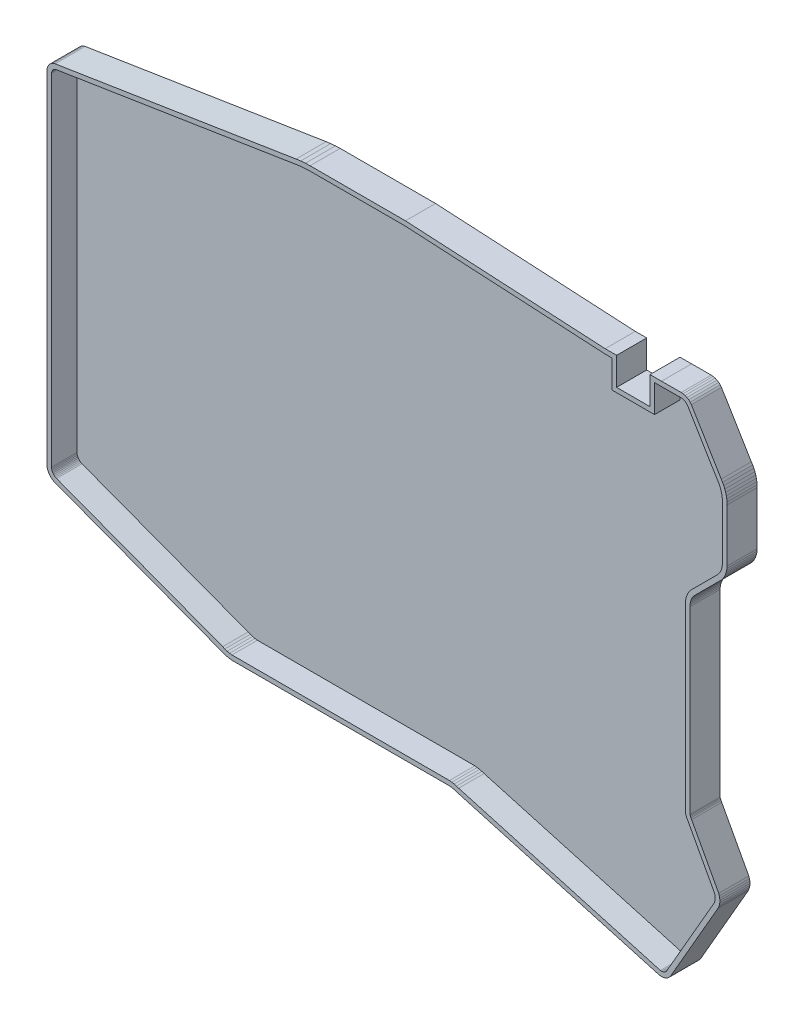
SolidWorks part; units mm, degrees
ref_plane "Plan de face" through (0, 0, 0) normal (0, 0, 1) x (1, 0, 0)
ref_plane "Plan de dessus" through (0, 0, 0) normal (0, 1, 0) x (1, 0, 0)
ref_plane "Plan de droite" through (0, 0, 0) normal (1, 0, 0) x (0, 0, -1)
sketch "Esquisse1" plane through (0, 0, 0) normal (0, 0, 1) x (1, 0, 0)
  line L182 (121.8175, 7.4929) -> (119.3447, 7.4929)
  line L183 (121.8175, 1.4929) -> (121.8175, 7.4929)
  line L184 (129.0175, 1.4929) -> (121.8175, 1.4929)
  line L185 (129.0175, 7.4929) -> (129.0175, 1.4929)
  line L186 (131.5156, 7.4929) -> (129.0175, 7.4929)
  line L187 (135.7674, 7.5091) -> (131.5156, 7.4929)
  line L188 (136.1661, 7.4784) -> (135.7674, 7.5091)
  line L189 (136.5947, 7.3735) -> (136.1661, 7.4784)
  line L190 (137.0006, 7.2004) -> (136.5947, 7.3735)
  line L191 (137.373, 6.9638) -> (137.0006, 7.2004)
  line L192 (137.702, 6.6698) -> (137.373, 6.9638)
  line L193 (137.9703, 6.337) -> (137.702, 6.6698)
  line L194 (144.4337, -4.377) -> (137.9703, 6.337)
  line L195 (144.7093, -4.8194) -> (144.4337, -4.377)
  line L196 (144.9711, -5.3219) -> (144.7093, -4.8194)
  line L197 (145.1938, -5.8429) -> (144.9711, -5.3219)
  line L198 (145.3759, -6.3795) -> (145.1938, -5.8429)
  line L199 (145.5165, -6.9284) -> (145.3759, -6.3795)
  line L200 (145.6147, -7.4865) -> (145.5165, -6.9284)
  line L201 (145.6698, -8.0504) -> (145.6147, -7.4865)
  line L202 (145.6811, -8.5891) -> (145.6698, -8.0504)
  line L203 (145.6811, -20.0309) -> (145.6811, -8.5891)
  line L204 (145.652, -20.495) -> (145.6811, -20.0309)
  line L205 (145.5768, -20.9698) -> (145.652, -20.495)
  line L206 (145.4573, -21.4355) -> (145.5768, -20.9698)
  line L207 (145.2944, -21.8878) -> (145.4573, -21.4355)
  line L208 (145.0897, -22.3228) -> (145.2944, -21.8878)
  line L209 (144.845, -22.7366) -> (145.0897, -22.3228)
  line L210 (144.5439, -23.151) -> (144.845, -22.7366)
  line L211 (138.4549, -29.2401) -> (144.5439, -23.151)
  line L212 (138.2752, -29.504) -> (138.4549, -29.2401)
  line L213 (138.0972, -29.8255) -> (138.2752, -29.504)
  line L214 (137.9495, -30.162) -> (138.0972, -29.8255)
  line L215 (137.8333, -30.5106) -> (137.9495, -30.162)
  line L216 (137.7496, -30.8685) -> (137.8333, -30.5106)
  line L217 (137.6991, -31.2325) -> (137.7496, -30.8685)
  line L218 (137.6811, -31.6225) -> (137.6991, -31.2325)
  line L219 (137.6811, -70.4918) -> (137.6811, -31.6225)
  line L220 (138.0267, -71.311) -> (137.8765, -71.0588)
  line L221 (143.8802, -82.1602) -> (138.0267, -71.311)
  line L222 (144.0173, -82.5853) -> (143.8802, -82.1602)
  line L223 (144.0963, -82.9931) -> (144.0173, -82.5853)
  line L224 (144.1256, -83.4074) -> (144.0963, -82.9931)
  line L225 (144.1049, -83.8223) -> (144.1256, -83.4074)
  line L226 (144.0343, -84.2316) -> (144.1049, -83.8223)
  line L227 (143.9151, -84.6295) -> (144.0343, -84.2316)
  line L228 (143.7508, -85.0055) -> (143.9151, -84.6295)
  line L229 (133.4297, -102.9289) -> (143.7508, -85.0055)
  line L230 (133.1808, -103.2268) -> (133.4297, -102.9289)
  line L231 (132.8911, -103.4768) -> (133.1808, -103.2268)
  line L232 (132.5648, -103.6766) -> (132.8911, -103.4768)
  line L233 (132.2104, -103.821) -> (132.5648, -103.6766)
  line L234 (131.8374, -103.9061) -> (132.2104, -103.821)
  line L235 (131.4555, -103.9297) -> (131.8374, -103.9061)
  line L236 (131.0689, -103.8905) -> (131.4555, -103.9297)
  line L237 (87.3868, -91.5555) -> (131.0689, -103.8905)
  line L238 (86.9098, -91.3963) -> (87.3868, -91.5555)
  line L239 (86.4791, -91.2848) -> (86.9098, -91.3963)
  line L240 (86.0417, -91.2031) -> (86.4791, -91.2848)
  line L241 (85.6232, -91.1544) -> (86.0417, -91.2031)
  line L242 (38.616, -91.1544) -> (85.6232, -91.1544)
  line L243 (37.9876, -91.0722) -> (38.616, -91.1544)
  line L244 (37.3875, -90.9356) -> (37.9876, -91.0722)
  line L245 (36.8028, -90.7435) -> (37.3875, -90.9356)
  line L246 (36.305, -90.5265) -> (36.8028, -90.7435)
  line L247 (0.3698, -77.0008) -> (36.305, -90.5265)
  line L248 (0.0324, -76.8325) -> (0.3698, -77.0008)
  line L249 (-0.2944, -76.6053) -> (0.0324, -76.8325)
  line L250 (-0.5849, -76.3334) -> (-0.2944, -76.6053)
  line L251 (-0.8332, -76.0225) -> (-0.5849, -76.3334)
  line L252 (-1.0341, -75.679) -> (-0.8332, -76.0225)
  line L253 (-1.1834, -75.3102) -> (-1.0341, -75.679)
  line L254 (-1.278, -74.9237) -> (-1.1834, -75.3102)
  line L255 (-1.3136, -74.552) -> (-1.278, -74.9237)
  line L256 (-1.2866, -0.6698) -> (-1.3136, -74.552)
  line L257 (-1.2348, -0.2816) -> (-1.2866, -0.6698)
  line L258 (-1.101, 0.1177) -> (-1.2348, -0.2816)
  line L259 (-0.8938, 0.4844) -> (-1.101, 0.1177)
  line L260 (-0.6208, 0.805) -> (-0.8938, 0.4844)
  line L261 (-0.2919, 1.0681) -> (-0.6208, 0.805)
  line L262 (0.0809, 1.2639) -> (-0.2919, 1.0681)
  line L263 (0.4579, 1.3776) -> (0.0809, 1.2639)
  line L264 (52.5355, 9.5898) -> (0.4579, 1.3776)
  line L265 (53.5332, 9.7263) -> (52.5355, 9.5898)
  line L266 (54.5522, 9.8124) -> (53.5332, 9.7263)
  line L267 (55.5648, 9.8456) -> (54.5522, 9.8124)
  line L268 (76.1838, 9.8456) -> (55.5648, 9.8456)
  line L269 (119.3447, 7.4929) -> (76.1838, 9.8456)
  line L270 (121.8175, 7.4929) -> (119.3447, 7.4929)
  line L271 (121.8175, 1.4929) -> (121.8175, 7.4929)
  line L272 (129.0175, 1.4929) -> (121.8175, 1.4929)
  line L273 (129.0175, 7.4929) -> (129.0175, 1.4929)
  line L274 (131.5156, 7.4929) -> (129.0175, 7.4929)
  line L275 (135.7674, 7.5091) -> (131.5156, 7.4929)
  line L276 (136.1661, 7.4784) -> (135.7674, 7.5091)
  line L277 (136.5947, 7.3735) -> (136.1661, 7.4784)
  line L278 (137.0006, 7.2004) -> (136.5947, 7.3735)
  line L279 (137.373, 6.9638) -> (137.0006, 7.2004)
  line L280 (137.702, 6.6698) -> (137.373, 6.9638)
  line L281 (137.9703, 6.337) -> (137.702, 6.6698)
  line L282 (144.4337, -4.377) -> (137.9703, 6.337)
  line L283 (144.7093, -4.8194) -> (144.4337, -4.377)
  line L284 (144.9711, -5.3219) -> (144.7093, -4.8194)
  line L285 (145.1938, -5.8429) -> (144.9711, -5.3219)
  line L286 (145.3759, -6.3795) -> (145.1938, -5.8429)
  line L287 (145.5165, -6.9284) -> (145.3759, -6.3795)
  line L288 (145.6147, -7.4865) -> (145.5165, -6.9284)
  line L289 (145.6698, -8.0504) -> (145.6147, -7.4865)
  line L290 (145.6811, -8.5891) -> (145.6698, -8.0504)
  line L291 (145.6811, -20.0309) -> (145.6811, -8.5891)
  line L292 (145.652, -20.495) -> (145.6811, -20.0309)
  line L293 (145.5768, -20.9698) -> (145.652, -20.495)
  line L294 (145.4573, -21.4355) -> (145.5768, -20.9698)
  line L295 (145.2944, -21.8878) -> (145.4573, -21.4355)
  line L296 (145.0897, -22.3228) -> (145.2944, -21.8878)
  line L297 (144.845, -22.7366) -> (145.0897, -22.3228)
  line L298 (144.5439, -23.151) -> (144.845, -22.7366)
  line L299 (138.4549, -29.2401) -> (144.5439, -23.151)
  line L300 (138.2752, -29.504) -> (138.4549, -29.2401)
  line L301 (138.0972, -29.8255) -> (138.2752, -29.504)
  line L302 (137.9495, -30.162) -> (138.0972, -29.8255)
  line L303 (137.8333, -30.5106) -> (137.9495, -30.162)
  line L304 (137.7496, -30.8685) -> (137.8333, -30.5106)
  line L305 (137.6991, -31.2325) -> (137.7496, -30.8685)
  line L306 (137.6811, -31.6225) -> (137.6991, -31.2325)
  line L307 (137.6811, -70.4918) -> (137.6811, -31.6225)
  line L308 (138.0267, -71.311) -> (137.8765, -71.0588)
  line L309 (143.8802, -82.1602) -> (138.0267, -71.311)
  line L310 (144.0173, -82.5853) -> (143.8802, -82.1602)
  line L311 (144.0963, -82.9931) -> (144.0173, -82.5853)
  line L312 (144.1256, -83.4074) -> (144.0963, -82.9931)
  line L313 (144.1049, -83.8223) -> (144.1256, -83.4074)
  line L314 (144.0343, -84.2316) -> (144.1049, -83.8223)
  line L315 (143.9151, -84.6295) -> (144.0343, -84.2316)
  line L316 (143.7508, -85.0055) -> (143.9151, -84.6295)
  line L317 (133.4297, -102.9289) -> (143.7508, -85.0055)
  line L318 (133.1808, -103.2268) -> (133.4297, -102.9289)
  line L319 (132.8911, -103.4768) -> (133.1808, -103.2268)
  line L320 (132.5648, -103.6766) -> (132.8911, -103.4768)
  line L321 (132.2104, -103.821) -> (132.5648, -103.6766)
  line L322 (131.8374, -103.9061) -> (132.2104, -103.821)
  line L323 (131.4555, -103.9297) -> (131.8374, -103.9061)
  line L324 (131.0689, -103.8905) -> (131.4555, -103.9297)
  line L325 (87.3868, -91.5555) -> (131.0689, -103.8905)
  line L326 (86.9098, -91.3963) -> (87.3868, -91.5555)
  line L327 (86.4791, -91.2848) -> (86.9098, -91.3963)
  line L328 (86.0417, -91.2031) -> (86.4791, -91.2848)
  line L329 (85.6232, -91.1544) -> (86.0417, -91.2031)
  line L330 (38.616, -91.1544) -> (85.6232, -91.1544)
  line L331 (37.9876, -91.0722) -> (38.616, -91.1544)
  line L332 (37.3875, -90.9356) -> (37.9876, -91.0722)
  line L333 (36.8028, -90.7435) -> (37.3875, -90.9356)
  line L334 (36.305, -90.5265) -> (36.8028, -90.7435)
  line L335 (0.3698, -77.0008) -> (36.305, -90.5265)
  line L336 (0.0324, -76.8325) -> (0.3698, -77.0008)
  line L337 (-0.2944, -76.6053) -> (0.0324, -76.8325)
  line L338 (-0.5849, -76.3334) -> (-0.2944, -76.6053)
  line L339 (-0.8332, -76.0225) -> (-0.5849, -76.3334)
  line L340 (-1.0341, -75.679) -> (-0.8332, -76.0225)
  line L341 (-1.1834, -75.3102) -> (-1.0341, -75.679)
  line L342 (-1.278, -74.9237) -> (-1.1834, -75.3102)
  line L343 (-1.3136, -74.552) -> (-1.278, -74.9237)
  line L344 (-1.2866, -0.6698) -> (-1.3136, -74.552)
  line L345 (-1.2348, -0.2816) -> (-1.2866, -0.6698)
  line L346 (-1.101, 0.1177) -> (-1.2348, -0.2816)
  line L347 (-0.8938, 0.4844) -> (-1.101, 0.1177)
  line L348 (-0.6208, 0.805) -> (-0.8938, 0.4844)
  line L349 (-0.2919, 1.0681) -> (-0.6208, 0.805)
  line L350 (0.0809, 1.2639) -> (-0.2919, 1.0681)
  line L351 (0.4579, 1.3776) -> (0.0809, 1.2639)
  line L352 (52.5355, 9.5898) -> (0.4579, 1.3776)
  line L353 (53.5332, 9.7263) -> (52.5355, 9.5898)
  line L354 (54.5522, 9.8124) -> (53.5332, 9.7263)
  line L355 (55.5648, 9.8456) -> (54.5522, 9.8124)
  line L356 (76.1838, 9.8456) -> (55.5648, 9.8456)
  line L357 (119.3447, 7.4929) -> (76.1838, 9.8456)
  line L358 (137.7162, -70.6526) -> (137.6811, -70.4918)
  line L359 (137.7162, -70.6526) -> (137.6811, -70.4918)
  line L360 (137.7855, -70.86) -> (137.7162, -70.6526)
  line L361 (137.7855, -70.86) -> (137.7162, -70.6526)
  line L362 (137.8765, -71.0588) -> (137.7855, -70.86)
  line L363 (137.8765, -71.0588) -> (137.7855, -70.86)
  dimension "D1" = 1
extrude "Boss.-Extru.1" add sketch "Esquisse1" against normal blind 6.5
shell "Coque1" thickness 1
